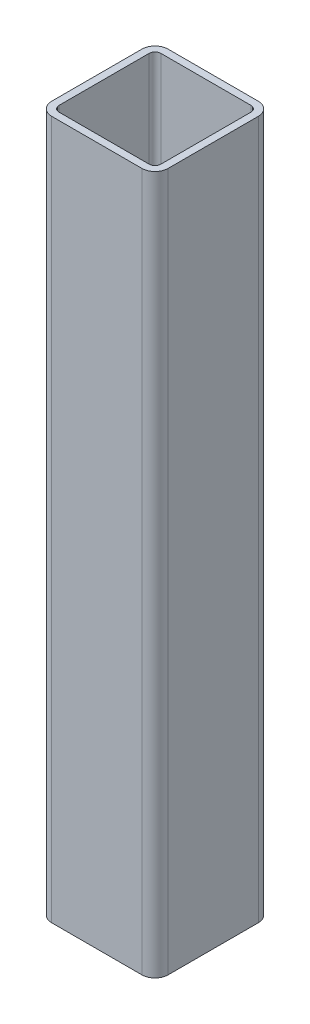
SolidWorks part; units mm, degrees
ref_plane "Front Plane" through (0, 0, 0) normal (0, 0, 1) x (1, 0, 0)
ref_plane "Top Plane" through (0, 0, 0) normal (0, 1, 0) x (1, 0, 0)
ref_plane "Right Plane" through (0, 0, 0) normal (1, 0, 0) x (0, 0, -1)
sketch "Sketch1" plane through (0, 0, 0) normal (0, 1, 0) x (1, 0, 0)
  line L0 (-19.685, 25.4) -> (19.685, 25.4)
  line L1 (-19.685, -22.225) -> (19.685, -22.225)
  line L2 (-22.225, -19.685) -> (-22.225, 19.685)
  line L3 (-19.685, 22.225) -> (19.685, 22.225)
  line L4 (22.225, -19.685) -> (22.225, 19.685)
  line L5 (-22.225, -22.225) -> (22.225, 22.225) construction
  line L6 (-22.225, 22.225) -> (22.225, -22.225) construction
  line L7 (25.4, -19.685) -> (25.4, 19.685)
  line L8 (-19.685, -25.4) -> (19.685, -25.4)
  line L9 (-25.4, -19.685) -> (-25.4, 19.685)
  arc A0 (-19.685, -22.225) -> (-22.225, -19.685) centre (-19.685, -19.685) cw
  arc A1 (19.685, -22.225) -> (22.225, -19.685) centre (19.685, -19.685) ccw
  arc A2 (19.685, 22.225) -> (22.225, 19.685) centre (19.685, 19.685) cw
  arc A3 (-22.225, 19.685) -> (-19.685, 22.225) centre (-19.685, 19.685) cw
  arc A4 (19.685, 25.4) -> (25.4, 19.685) centre (19.685, 19.685) cw
  arc A5 (19.685, -25.4) -> (25.4, -19.685) centre (19.685, -19.685) ccw
  arc A6 (-19.685, -25.4) -> (-25.4, -19.685) centre (-19.685, -19.685) cw
  arc A7 (-25.4, 19.685) -> (-19.685, 25.4) centre (-19.685, 19.685) cw
  point P0 (0, 0)
  dimension "D3" = 2.54
  dimension "D1" = 44.45
  dimension "D2" = 44.45
  dimension "D4" = 3.175
extrude "Boss-Extrude1" add sketch "Sketch1" along normal mid plane 304.8
